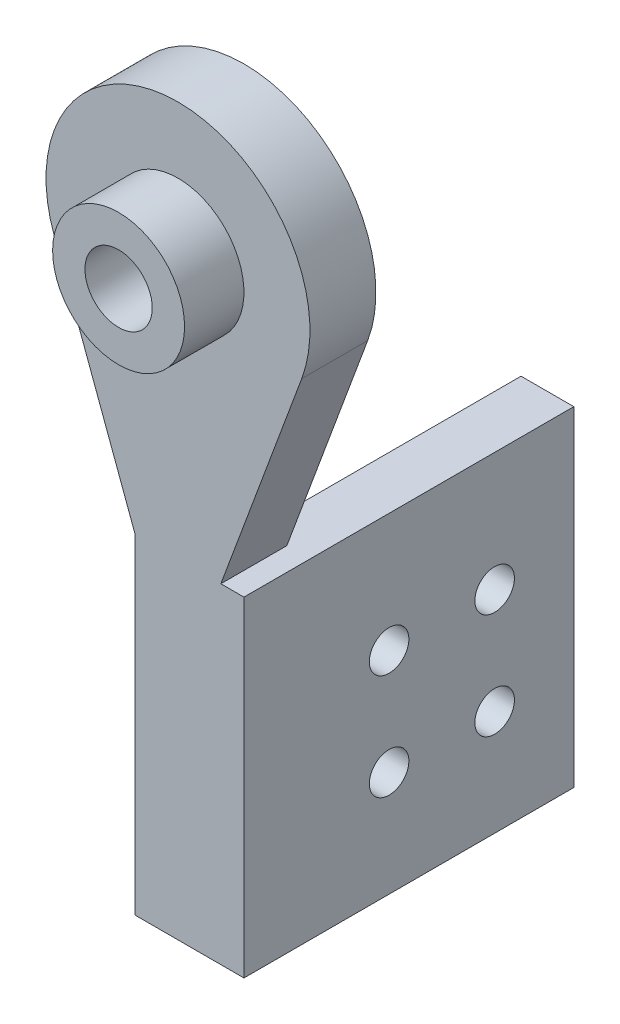
SolidWorks part; units mm, degrees
ref_plane "前视基准面" through (0, 0, 0) normal (0, 0, 1) x (1, 0, 0)
ref_plane "上视基准面" through (0, 0, 0) normal (0, 1, 0) x (1, 0, 0)
ref_plane "右视基准面" through (0, 0, 0) normal (1, 0, 0) x (0, 0, -1)
sketch "草图1" plane through (0, 0, 0) normal (0, 0, 1) x (1, 0, 0)
  line L0 (-3.5812, -8.028) -> (-3.5812, -12.6119)
  line L1 (-3.5812, 12.3881) -> (2.9188, 12.3881)
  line L2 (-3.5812, 12.3881) -> (-3.5812, -8.028)
  line L4 (2.9188, 12.3881) -> (2.9188, -6.6419)
  line L5 (-0.0812, -6.5) -> (-0.0812, 9.528) construction
  line L6 (-3.5812, 2.1801) -> (2.4188, 2.1801) construction
  line L7 (-3.5812, -12.6119) -> (2.9188, -12.6119)
  line L8 (2.9188, -12.6119) -> (2.9188, -6.6419)
  circle A0 centre (-0.0812, 8.2375) radius 1.25
  circle A1 centre (-0.0812, 2.7875) radius 1.25
  circle A2 centre (-0.0812, -2.6625) radius 1.25
  circle A3 centre (-0.0008, -8.1119) radius 1.25
  point P0 (0, 0)
  dimension "D3" = 2.5
  dimension "D4" = 2.5
  dimension "D5" = 2.5
  dimension "D1" = 2.5
  dimension "D2" = 4.5
  dimension "D6" = 5.45
  dimension "D7" = 6.5
  dimension "D8" = 5.45
  dimension "D9" = 5.45
  dimension "D10" = 3
  dimension "D11" = 25
extrude "凸台-拉伸1" add sketch "草图1" along normal blind 5
sketch "草图2" plane through (-3.5812, 0, 0) normal (-1, 0, 0) x (0, 0, 1)
  line L1 (0, 12.3881) -> (5, 12.3881)
  line L2 (0, 12.3881) -> (0, -12.6119)
  line L3 (0, -12.6119) -> (5, -12.6119)
  line L4 (5, 12.3881) -> (5, -12.6119)
extrude "凸台-拉伸2" add sketch "草图2" along normal blind 4
sketch "草图3" plane through (0, 0, 0) normal (0, 0, -1) x (-1, 0, 0)
  line L0 (-2.9188, 12.3881) -> (7.5812, 12.3881) construction
  line L1 (3.5812, 12.3881) -> (7.5812, 12.3881)
  line L2 (3.5812, 12.3881) -> (3.5812, -12.6119)
  line L3 (3.5812, -12.6119) -> (7.5812, -12.6119)
  line L4 (7.5812, 12.3881) -> (7.5812, -12.6119)
  line L5 (7.5812, 12.3881) -> (7.5812, -12.6119) construction
  line L6 (7.5812, -12.6119) -> (-2.9188, -12.6119) construction
  dimension "D1" = 4
extrude "凸台-拉伸3" add sketch "草图3" along normal blind 20 contours L2 L1 L4 L3
sketch "草图4" plane through (-3.5812, 0, 0) normal (1, 0, 0) x (0, 0, -1)
  line L0 (-0.5142, -0.6119) -> (22.6758, -0.6119) construction
  line L1 (10, 9.3991) -> (10, -15.8743) construction
  line L2 (20, 12.3881) -> (0, 12.3881) construction
  circle A0 centre (6, 3.3881) radius 1.5
  circle A1 centre (14, 3.3881) radius 1.5
  circle A2 centre (14, -4.6119) radius 1.5
  circle A3 centre (6, -4.6119) radius 1.5
  dimension "D1" = 3
  dimension "D2" = 4
  dimension "D3" = 4
  dimension "D4" = 9
extrude "切除-拉伸1" cut sketch "草图4" against normal blind 20
sketch "草图7" plane through (0, 0, 5) normal (0, 0, 1) x (1, 0, 0)
  circle A0 centre (-0.0812, 8.2375) radius 1.25
  circle A1 centre (-0.0812, 2.7875) radius 1.25
  circle A2 centre (-0.0812, -2.6625) radius 1.25
  circle A3 centre (-0.0008, -8.1119) radius 1.25
extrude "凸台-拉伸4" add sketch "草图7" against normal blind 5
sketch "草图8" plane through (0, 0, 5) normal (0, 0, 1) x (1, 0, 0)
  line L4 (-9.7078, 28.9112) -> (-3.5812, 12.3881)
  line L5 (9.0454, 28.9113) -> (2.9188, 12.3881)
  line L11 (-3.5812, 12.3881) -> (2.9188, 12.3881)
  circle A2 centre (6.6688, 32.3881) radius 1.5
  circle A3 centre (-0.3313, 39.388) radius 1.5
  circle A4 centre (-7.3313, 32.388) radius 1.5
  circle A5 centre (-0.3313, 25.388) radius 1.5
  circle A6 centre (-0.3313, 32.388) radius 4
  arc A7 (-9.7078, 28.9112) -> (9.0454, 28.9113) centre (-0.3313, 32.388) cw
  line M15 (2.9188, 12.3881) -> (-7.5812, 12.3881)
extrude "凸台-拉伸5" add sketch "草图8" against normal blind 5 contours A7 L4 L5 A6 A5 A4 A3 A2 M15
sketch "草图14" plane through (2.9188, 0, 0) normal (1, 0, 0) x (0, 0, -1)
  line L1 (-5, -12.6119) -> (20, -12.6119)
  line L2 (-5, -12.6119) -> (-5, 12.3881)
  line L3 (-5, 12.3881) -> (20, 12.3881)
  line L4 (20, -12.6119) -> (20, 12.3881)
  circle A0 centre (6, 3.3881) radius 1.5
  circle A1 centre (14, 3.3881) radius 1.5
  circle A2 centre (14, -4.6119) radius 1.5
  circle A3 centre (6, -4.6119) radius 1.5
extrude "凸台-拉伸9" add sketch "草图14" along normal blind 4 contours L2 L1 L4 L3 | A0 | A3 | A2 | A1
sketch "草图15" plane through (0, 0, -20) normal (0, 0, -1) x (-1, 0, 0)
  line L1 (3.5812, 12.3881) -> (7.5812, 12.3881)
  line L2 (3.5812, 12.3881) -> (3.5812, -12.6119)
  line L3 (3.5812, -12.6119) -> (7.5812, -12.6119)
  line L4 (7.5812, 12.3881) -> (7.5812, -12.6119)
extrude "切除-拉伸2" cut sketch "草图15" against normal blind 100
sketch "草图16" plane through (0, 0, 5) normal (0, 0, 1) x (1, 0, 0)
  circle A0 centre (-0.3313, 32.388) radius 10.0004
  circle A1 centre (-0.3313, 32.388) radius 2.55
extrude "凸台-拉伸10" add sketch "草图16" against normal blind 5
sketch "草图18" plane through (0, 0, 5) normal (0, 0, 1) x (1, 0, 0)
  circle A0 centre (-0.3313, 32.388) radius 2.55
  circle A1 centre (-0.3313, 32.388) radius 5
extrude "凸台-拉伸11" add sketch "草图18" along normal blind 4.5
sketch "草图19" plane through (-3.5812, 0, 0) normal (-1, 0, 0) x (0, 0, 1)
  line L1 (5, 12.3881) -> (-20, 12.3881)
  line L2 (5, 12.3881) -> (5, -12.6119)
  line L3 (5, -12.6119) -> (-20, -12.6119)
  line L4 (-20, 12.3881) -> (-20, -12.6119)
  circle A0 centre (-14, 3.3881) radius 1.5
  circle A1 centre (-6, 3.3881) radius 1.5
  circle A2 centre (-14, -4.6119) radius 1.5
  circle A3 centre (-6, -4.6119) radius 1.5
extrude "凸台-拉伸12" add sketch "草图19" along normal blind 4
sketch "草图20" plane through (6.9188, 0, 0) normal (1, 0, 0) x (0, 0, -1)
  line L1 (-5, 12.3881) -> (20, 12.3881)
  line L2 (-5, 12.3881) -> (-5, -12.6119)
  line L3 (-5, -12.6119) -> (20, -12.6119)
  line L4 (20, 12.3881) -> (20, -12.6119)
extrude "切除-拉伸3" cut sketch "草图20" against normal blind 4
sketch "草图21" plane through (0, 0, 0) normal (0, 0, -1) x (-1, 0, 0)
  line L0 (0.3313, 32.388) -> (0.3313, -21.3344)
  line L2 (0.3313, 5.5268) -> (-0.6687, 5.5268)
  line L3 (-0.6687, 5.5268) -> (-0.6687, 12.3881)
  line L4 (-0.6687, 12.3881) -> (-4.6687, 12.3881)
  line L5 (3.5812, -12.6119) -> (-2.9188, -12.6119) construction
  line L6 (-4.6687, 12.3881) -> (-0.6687, 12.3881)
  line L7 (-4.6687, 12.3881) -> (-4.6687, -12.6119)
  line L8 (-4.6687, -12.6119) -> (-0.6687, -12.6119)
  line L9 (-0.6687, 12.3881) -> (-0.6687, -12.6119)
  line M10 (-2.9188, 12.3881) -> (-2.9188, -12.6119)
  line M11 (-2.9188, -12.6119) -> (3.5812, -12.6119)
extrude "凸台-拉伸13" add sketch "草图21" along normal blind 20 contours L9 L3 L4 M10 M11 | L7 L8 L4 M10
sketch "草图22" plane through (-7.5812, 0, 0) normal (-1, 0, 0) x (0, 0, 1)
  circle A0 centre (-14, 3.3881) radius 1.5
  circle A1 centre (-6, 3.3881) radius 1.5
  circle A2 centre (-14, -4.6119) radius 1.5
  circle A3 centre (-6, -4.6119) radius 1.5
extrude "切除-拉伸4" cut sketch "草图22" against normal blind 20
sketch "草图23" plane through (-7.5812, 0, 0) normal (-1, 0, 0) x (0, 0, 1)
  line L1 (-20, 12.3881) -> (5, 12.3881)
  line L2 (-20, 12.3881) -> (-20, -12.6119)
  line L3 (-20, -12.6119) -> (5, -12.6119)
  line L4 (5, 12.3881) -> (5, -12.6119)
extrude "切除-拉伸5" cut sketch "草图23" against normal blind 4
sketch "草图24" plane through (0, 0, 0) normal (0, 0, 1) x (1, 0, 0)
  line L1 (2.9188, 12.3881) -> (4.6687, 12.3881)
  line L2 (2.9188, 12.3881) -> (2.9188, -12.6119)
  line L3 (2.9188, -12.6119) -> (4.6687, -12.6119)
  line L4 (4.6687, 12.3881) -> (4.6687, -12.6119)
extrude "凸台-拉伸14" add sketch "草图24" along normal blind 5
